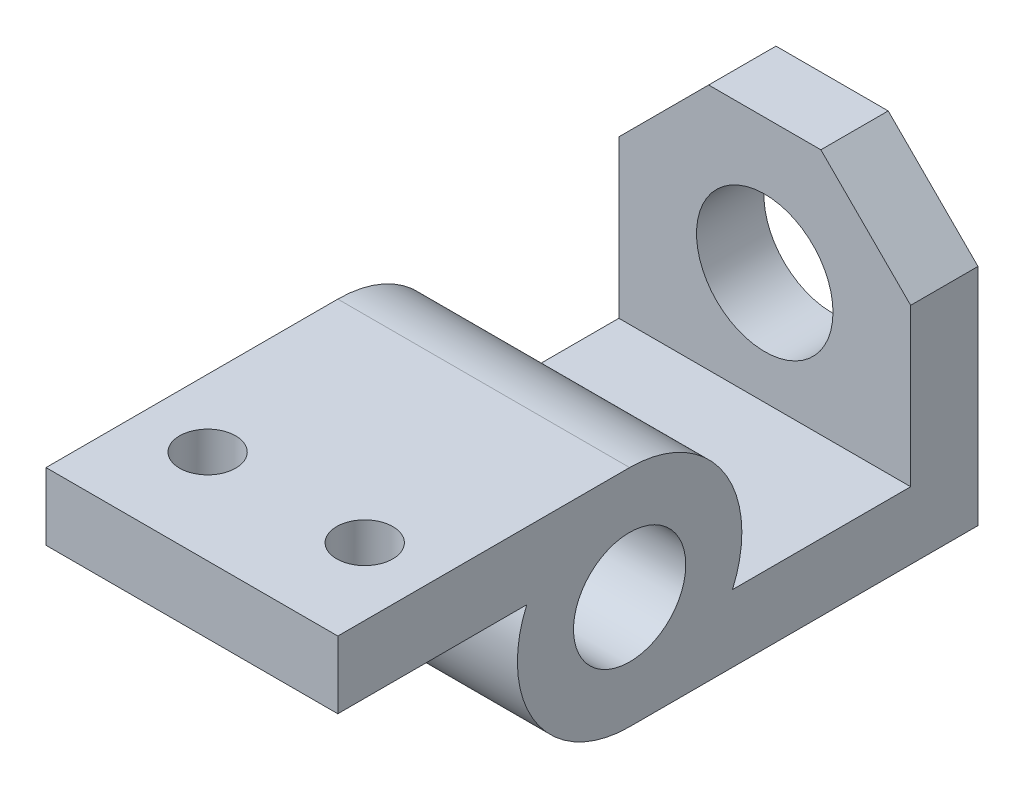
SolidWorks part; units mm, degrees
ref_plane "Front Plane" through (0, 0, 0) normal (0, 0, 1) x (1, 0, 0)
ref_plane "Top Plane" through (0, 0, 0) normal (0, 1, 0) x (1, 0, 0)
ref_plane "Right Plane" through (0, 0, 0) normal (1, 0, 0) x (0, 0, -1)
sketch "Sketch2" plane through (0, 0, 0) normal (1, 0, 0) x (0, 0, -1)
  line L0 (0, 31.75) -> (-82.55, 31.75)
  line L1 (-82.55, 31.75) -> (-82.55, 12.7)
  line L2 (-82.55, 12.7) -> (-29.0994, 12.7)
  line L3 (29.0994, -12.7) -> (79.502, -12.7)
  line L4 (79.502, -12.7) -> (79.502, 57.15)
  line L5 (79.502, 57.15) -> (98.552, 57.15)
  line L6 (98.552, 57.15) -> (98.552, -31.75)
  line L7 (98.552, -31.75) -> (0, -31.75)
  circle A0 centre (0, 0) radius 15.875
  arc A1 (0, 31.75) -> (29.0994, -12.7) centre (0, 0) cw
  arc A2 (0, -31.75) -> (-29.0994, 12.7) centre (0, 0) cw
  dimension "D1" = 31.75
  dimension "D2" = 31.75
  dimension "D3" = 31.75
  dimension "D4" = 19.05
  dimension "D5" = 98.552
  dimension "D6" = 181.102
  dimension "D7" = 19.05
  dimension "D8" = 88.9
  dimension "D9" = 19.05
extrude "Boss-Extrude1" add sketch "Sketch2" against normal blind 82.55 contours A2 L7 L6 L5 L4 L3 A1 L0 L1 L2 A0
sketch "Sketch4" plane through (0, 31.75, 0) normal (0, 1, 0) x (1, 0, 0)
  line L0 (0, 0) -> (0, -82.55) construction
  line L1 (-82.55, -82.55) -> (0, -82.55) construction
  circle A0 centre (-63.5, -55.88) radius 7.9375
  circle A1 centre (-19.05, -55.88) radius 7.9375
  dimension "D1" = 15.875
  dimension "D2" = 15.875
  dimension "D3" = 44.45
  dimension "D4" = 19.05
  dimension "D5" = 26.67
extrude "Cut-Extrude1" cut sketch "Sketch4" against normal through all
sketch "Sketch5" plane through (0, 0, -79.502) normal (0, 0, 1) x (1, 0, 0)
  line L0 (0, -12.7) -> (0, 57.15) construction
  line L1 (-82.55, 57.15) -> (0, 57.15) construction
  line L2 (-82.55, -12.7) -> (-82.55, 57.15) construction
  line L3 (0, -12.7) -> (0, 57.15)
  line L4 (-82.55, 57.15) -> (0, 57.15)
  line L5 (-82.55, -12.7) -> (-82.55, 57.15)
  line L6 (-82.55, 31.75) -> (-57.15, 57.15)
  line L7 (-25.4, 57.15) -> (0, 31.75)
  circle A0 centre (-41.275, 19.05) radius 19.304
  line M3 (0, 57.15) -> (-82.55, 57.15)
  line M4 (-82.55, 57.15) -> (-82.55, -12.7)
  dimension "D1" = 38.608
  dimension "D2" = 38.1
  dimension "D3" = 41.275
  dimension "D4" = 25.4
  dimension "D5" = 25.4
  dimension "D6" = 25.4
  dimension "D7" = 25.4
extrude "Cut-Extrude2" cut sketch "Sketch5" against normal through all contours L6 L4 M4 | L7 L3 M3 | A0
